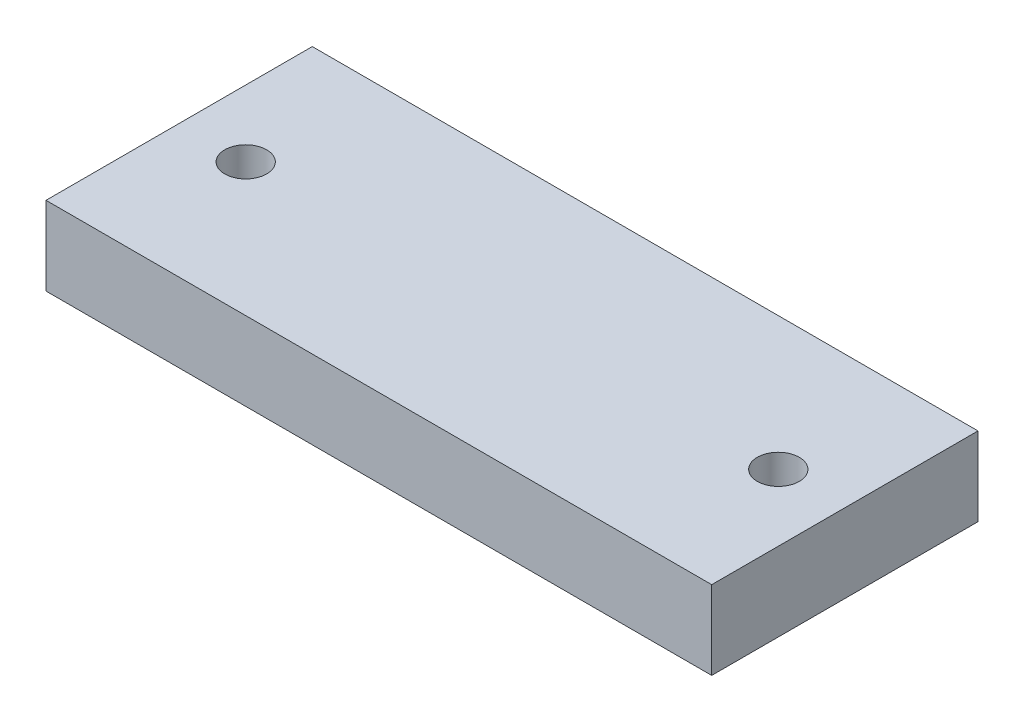
SolidWorks part; units mm, degrees
material "轻木"
ref_plane "Front" through (0, 0, 0) normal (0, 0, 1) x (1, 0, 0)
ref_plane "Top" through (0, 0, 0) normal (0, 1, 0) x (1, 0, 0)
ref_plane "Right" through (0, 0, 0) normal (1, 0, 0) x (0, 0, -1)
sketch "草图1" plane through (0, 0, 0) normal (0, 1, 0) x (1, 0, 0)
  line L1 (0, 0) -> (127, 0)
  line L2 (0, 0) -> (0, -50.8)
  line L3 (0, -50.8) -> (127, -50.8)
  line L4 (127, 0) -> (127, -50.8)
  circle A0 centre (12.7, -25.4) radius 4
  circle A2 centre (114.3, -25.4) radius 4
  point P7 (127, -25.4)
  point P8 (0, -25.4)
  dimension "D3" = 25.4
  dimension "D4" = 8
  dimension "D5" = 8
  dimension "D6" = 12.7
  dimension "D1" = 101.6
  dimension "D2" = 50.8
  dimension "D7" = 25.4
  dimension "D8" = 12.7
extrude "凸台-拉伸1" add sketch "草图1" along normal blind 15
